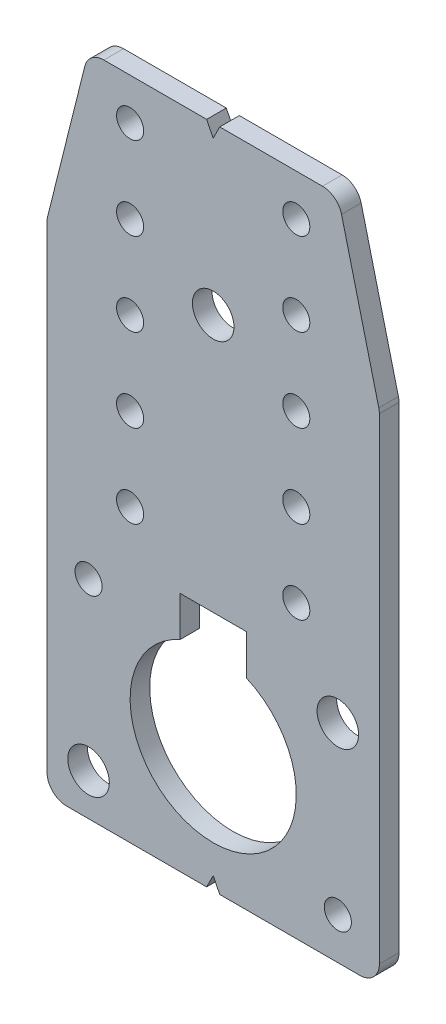
SolidWorks part; units mm, degrees
ref_plane "Front Plane" through (0, 0, 0) normal (0, 0, 1) x (1, 0, 0)
ref_plane "Top Plane" through (0, 0, 0) normal (0, 1, 0) x (1, 0, 0)
ref_plane "Right Plane" through (0, 0, 0) normal (1, 0, 0) x (0, 0, -1)
sketch "Sketch1" plane through (0, 0, 0) normal (0, 0, 1) x (1, 0, 0)
  line L0 (-19.05, 82.55) -> (19.05, 82.55)
  line L1 (-25.4, 57.15) -> (25.4, 57.15) construction
  line L2 (-25.4, 57.15) -> (-25.4, -19.05)
  line L3 (-25.4, -19.05) -> (25.4, -19.05)
  line L4 (25.4, 57.15) -> (25.4, -19.05)
  line L5 (-19.05, 82.55) -> (-25.4, 57.15)
  line L6 (19.05, 82.55) -> (25.4, 57.15)
  line L7 (-25.4, -12.7) -> (-19.05, -12.7) construction
  line L8 (-19.05, -12.7) -> (-19.05, -19.05) construction
  line L9 (19.05, 19.05) -> (19.05, 12.7) construction
  line L10 (-25.4, 19.05) -> (25.4, 19.05) construction
  line L11 (-25.4, 19.05) -> (-25.4, -19.05) construction
  line L12 (-25.4, -19.05) -> (25.4, -19.05) construction
  line L13 (25.4, 19.05) -> (25.4, -19.05) construction
  line L14 (-25.4, 19.05) -> (25.4, -19.05) construction
  line L15 (-25.4, -19.05) -> (25.4, 19.05) construction
  line L16 (19.05, 12.7) -> (25.4, 12.7) construction
  line L17 (-25.4, 12.7) -> (-19.05, 12.7) construction
  line L18 (-19.05, 12.7) -> (-19.05, 19.05) construction
  line L19 (19.05, -19.05) -> (19.05, -12.7) construction
  line L20 (19.05, -12.7) -> (25.4, -12.7) construction
  line L21 (0, 82.55) -> (0, 19.05) construction
  line L22 (12.7, 57.15) -> (12.7, 19.05) construction
  circle A0 centre (0, 0) radius 12.7
  circle A1 centre (-19.05, -12.7) radius 3.175
  circle A2 centre (19.05, 12.7) radius 3.175
  circle A3 centre (-19.05, 12.7) radius 2.07
  circle A4 centre (19.05, -12.7) radius 2.07
  circle A5 centre (0, 57.15) radius 3.175
  circle A6 centre (12.7, 25.4) radius 2.07
  circle A8 centre (12.7, 38.1) radius 2.07
  circle A9 centre (12.7, 50.8) radius 2.07
  circle A10 centre (12.7, 63.5) radius 2.07
  circle A11 centre (12.7, 76.2) radius 2.07
  circle A12 centre (-12.7, 25.4) radius 2.07
  circle A13 centre (-12.7, 38.1) radius 2.07
  circle A14 centre (-12.7, 50.8) radius 2.07
  circle A15 centre (-12.7, 63.5) radius 2.07
  circle A16 centre (-12.7, 76.2) radius 2.07
  point P8 (0, -19.05)
  point P10 (0, 82.55)
  dimension "D1" = 25.4
  dimension "D2" = 19.05
  dimension "D8" = 6.35
  dimension "D9" = 4.14
  dimension "D3" = 50.8
  dimension "D4" = 76.2
  dimension "D5" = 25.4
  dimension "D6" = 6.35
  dimension "D7" = 6.35
  dimension "D10" = 12.7
  dimension "D11" = 6.35
  dimension "D13" = 12.7
  dimension "D12" = 5
extrude "Boss-Extrude1" add sketch "Sketch1" along normal mid plane 3 contours L5 L2 L3 L4 L6 L0
fillet "Fillet1" radius 3 6 edges at (25.4, 57.15, 0) (25.4, -19.05, 0) (-25.4, -19.05, 0) (-25.4, 57.15, 0) (-19.05, 82.55, 0) (19.05, 82.55, 0)
sketch "Sketch2" plane through (0, 0, 1.5) normal (0, 0, 1) x (1, 0, 0)
  line L0 (0, 82.55) -> (0, -19.05) construction
  line L1 (16.7077, 82.55) -> (-16.7077, 82.55) construction
  line L2 (-22.4, -19.05) -> (22.4, -19.05) construction
  line L3 (-1, 82.55) -> (1, 82.55)
  line L4 (-1, 82.55) -> (0, 80.55)
  line L5 (1, 82.55) -> (0, 80.55)
  line L6 (0, 31.75) -> (-25.4, 31.75) construction
  line L7 (-25.4, 56.7807) -> (-25.4, -16.05) construction
  line L8 (-1, -19.05) -> (1, -19.05)
  line L9 (-1, -19.05) -> (0, -17.05)
  line L10 (1, -19.05) -> (0, -17.05)
  line L11 (-5.08, 17.78) -> (5.08, 17.78)
  line L12 (5.08, 17.78) -> (5.08, 11.6397)
  line L13 (-5.08, 17.78) -> (-5.08, 11.6397)
  circle A0 centre (0, 0) radius 12.7 construction
  arc A1 (0, -12.7) -> (-5.08, 11.6397) centre (0, 0) ccw
  arc A2 (-5.08, 11.6397) -> (0, -12.7) centre (0, 0) ccw construction
  point P8 (0, 82.55)
  point P20 (0, 17.78)
  circle M15 centre (0, 0) radius 12.7
  line M20 (16.7077, 82.55) -> (-16.7077, 82.55)
  line M26 (-22.4, -19.05) -> (22.4, -19.05)
  dimension "D1" = 2
  dimension "D2" = 2
  dimension "D3" = 10.16
  dimension "D4" = 17.78
extrude "Cut-Extrude1" cut sketch "Sketch2" against normal blind 3 contours L11 L13 L12 M15 | L10 L9 M26 | L5 L4 M20
